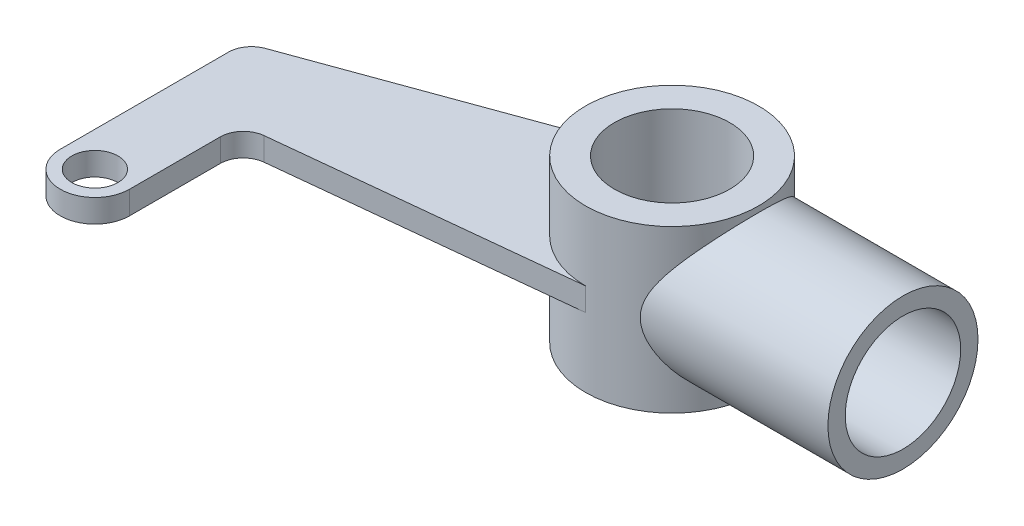
SolidWorks part; units mm, degrees
ref_plane "前基準面" through (0, 0, 0) normal (0, 0, 1) x (1, 0, 0)
ref_plane "上基準面" through (0, 0, 0) normal (0, 1, 0) x (1, 0, 0)
ref_plane "右基準面" through (0, 0, 0) normal (1, 0, 0) x (0, 0, -1)
sketch "草圖1" plane through (0, 0, 0) normal (0, 1, 0) x (1, 0, 0)
  circle A0 centre (0, 0) radius 37.5
  circle A1 centre (0, 0) radius 25
  dimension "D1" = 50
  dimension "D2" = 75
extrude "填料-伸長1" add sketch "草圖1" along normal blind 70
sketch "草圖2" plane through (0, 0, 0) normal (1, 0, 0) x (0, 0, -1)
  line L1 (25, 70) -> (-25, 70) construction
  circle A0 centre (0, 35) radius 32.5
  circle A1 centre (0, 35) radius 25
  point P2 (0, 35.875)
  point P8 (0, 35)
  dimension "D1" = 65
  dimension "D2" = 50
  dimension "D3" = 35
extrude "填料-伸長2" add sketch "草圖2" along normal blind 100
sketch "草圖3" plane through (0, 70, 0) normal (0, 1, 0) x (1, 0, 0)
  circle A0 centre (0, 0) radius 25
extrude "除料-伸長1" cut sketch "草圖3" against normal blind 100
sketch "草圖4" plane through (100, 0, 0) normal (1, 0, 0) x (0, 0, -1)
  circle A0 centre (0, 35) radius 25
  dimension "D1" = 50
extrude "除料-伸長2" cut sketch "草圖4" against normal blind 100
sketch "草圖5" plane through (0, 0, 0) normal (0, 1, 0) x (1, 0, 0)
  line L0 (-12.8258, 35.2385) -> (-165, -20.1484)
  line L1 (-165, -20.1484) -> (-165, -100)
  line L2 (0, -37.5) -> (-135, -51.6891)
  line L3 (-135, -51.6891) -> (-135, -100)
  line L4 (0, 37.5) -> (-112.9621, 37.5) construction
  line L5 (-135, -100) -> (-165, -100) construction
  circle A0 centre (0, 0) radius 37.5 construction
  circle A1 centre (-150, -100) radius 15
  circle A2 centre (-150, -100) radius 10
  circle A3 centre (0, 0) radius 37.5 construction
  arc A4 (-12.8258, 35.2385) -> (0, -37.5) centre (0, 0) ccw
  point P6 (-135, -50.1504)
  dimension "D1" = 150
  dimension "D6" = 20
  dimension "D2" = 30
  dimension "D3" = 135
  dimension "D4" = 20
  dimension "D5" = 100
  dimension "D7" = 6
extrude "填料-伸長3" add sketch "草圖5" along normal mid plane 10 from offset 35
fillet "圓角2" radius 10 2 edges at (-135, 35, 51.6891) (-165, 35, 20.1484)
sketch "草圖6" plane through (0, 0, 0) normal (0, 1, 0) x (1, 0, 0)
  line L0 (0, 0) -> (136.7928, 0) construction
